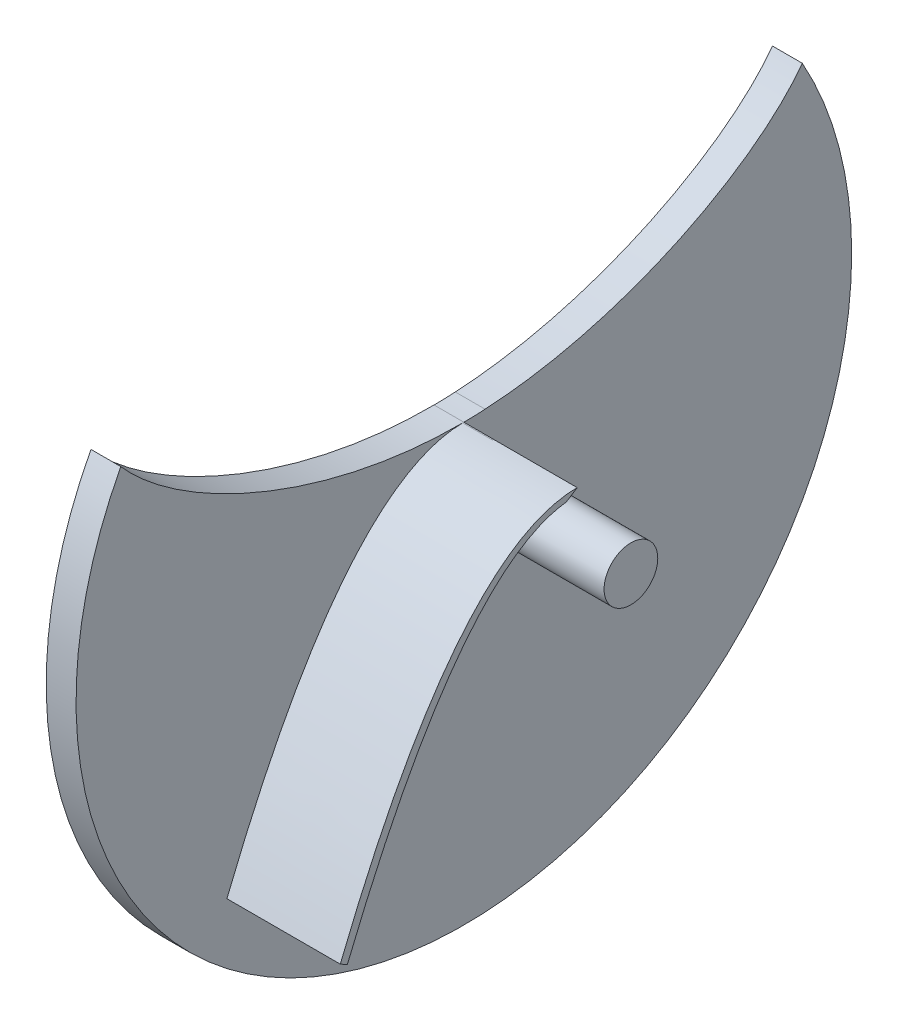
SolidWorks part; units mm, degrees
ref_plane "Front Plane" through (0, 0, 0) normal (0, 0, 1) x (1, 0, 0)
ref_plane "Top Plane" through (0, 0, 0) normal (0, 1, 0) x (1, 0, 0)
ref_plane "Right Plane" through (0, 0, 0) normal (1, 0, 0) x (0, 0, -1)
sketch "Sketch1" plane through (0, 0, 0) normal (1, 0, 0) x (0, 0, -1)
  circle A0 centre (0, 0) radius 65
  dimension "D1" = 130
extrude "Boss-Extrude1" add sketch "Sketch1" along normal blind 5
sketch "Sketch2" plane through (5, 0, 0) normal (1, 0, 0) x (0, 0, -1)
  circle A0 centre (0, 65) radius 57
  circle A1 centre (0, 0) radius 65 construction
  dimension "D1" = 114
extrude "Cut-Extrude1" cut sketch "Sketch2" against normal blind 5
sketch "Sketch3" plane through (5, 0, 0) normal (1, 0, 0) x (0, 0, -1)
  circle A0 centre (0, 0) radius 4.5
  dimension "D1" = 9
extrude "Boss-Extrude2" add sketch "Sketch3" along normal blind 28
sketch "Sketch4" plane through (5, 0, 0) normal (1, 0, 0) x (0, 0, -1)
  line L0 (-38.5288, -41.9542) -> (-39.7176, -41.2965)
  line L1 (-1.8343, 6.8325) -> (0, 8)
  arc A0 (-51.2287, 40.0077) -> (51.2287, 40.0077) centre (0, 65) ccw construction
  parabola Q0 (-39.7176, -41.2965) -> (0, 8) focus (0, 0) apex (0, 8)
  parabola Q1 (-38.5288, -41.9542) -> (-1.8343, 6.8325) focus (0, 0) apex (0.212, 6.9205)
extrude "Boss-Extrude3" add sketch "Sketch4" along normal blind 19 contours Q0 L1 Q1 L0
sketch "Sketch5" plane through (0, 0, 0) normal (-1, 0, 0) x (0, 0, 1)
  arc A0 (-51.2287, 40.0077) -> (51.2287, 40.0077) centre (0, 65) ccw construction
  spline S0 degree 3 poles (121.1268, 64.5898) (-117.4446, 63.9382) (0.7253, -12.4508) (121.1268, 64.5898) (-117.4446, 63.9382) (0.7253, -12.4508) knots -1 -0.737737 -0.466901 0 0.262263 0.533099 1 1.262263 1.533099 2 only from (-59.6113, 41.1618) to (-59.6113, 41.1618)
extrude "Cut-Extrude2" cut sketch "Sketch5" against normal blind 10
